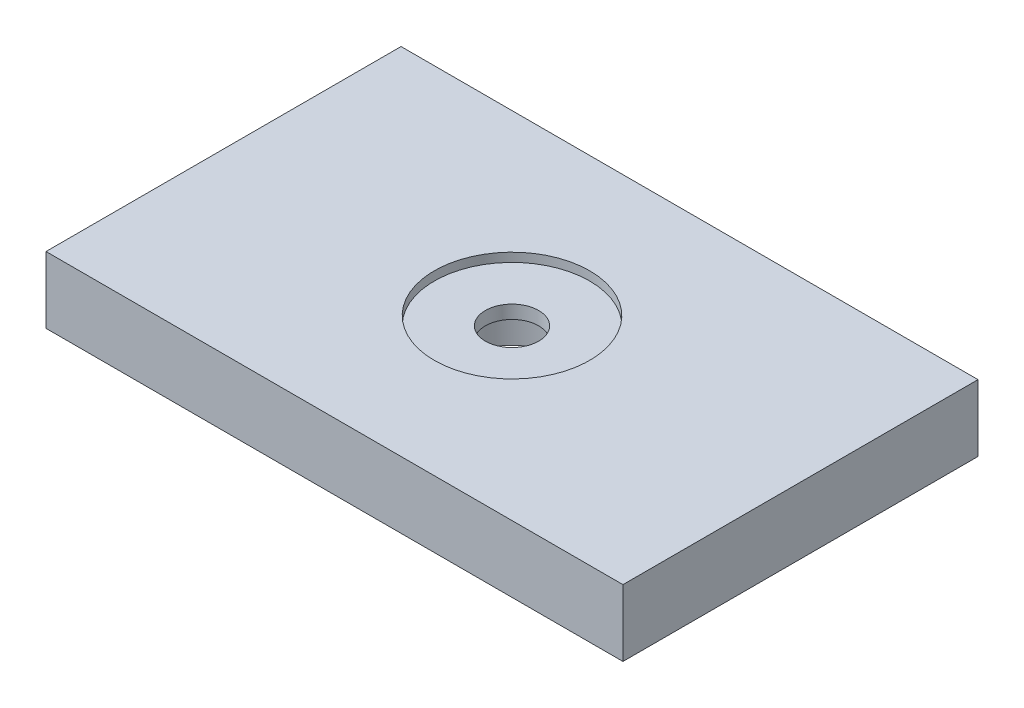
SolidWorks part; units mm, degrees
ref_plane "Спереди" through (0, 0, 0) normal (0, 0, 1) x (1, 0, 0)
ref_plane "Сверху" through (0, 0, 0) normal (0, 1, 0) x (1, 0, 0)
ref_plane "Справа" through (0, 0, 0) normal (1, 0, 0) x (0, 0, -1)
sketch "Эскиз4" plane through (0, 0, 0) normal (0, 1, 0) x (1, 0, 0)
  line L1 (-65, 40) -> (65, 40)
  line L2 (-65, 40) -> (-65, -40)
  line L3 (-65, -40) -> (65, -40)
  line L4 (65, 40) -> (65, -40)
  line L5 (-65, 40) -> (65, -40) construction
  line L6 (-65, -40) -> (65, 40) construction
  point P0 (0, 0)
extrude "Бобышка-Вытянуть3" add sketch "Эскиз4" along normal blind 15
sketch "Эскиз5" plane through (0, 15, 0) normal (0, 1, 0) x (1, 0, 0)
  circle A0 centre (0, 0) radius 17.5
extrude "Вырез-Вытянуть1" cut sketch "Эскиз5" against normal blind 2
sketch "Эскиз6" plane through (0, 0, 0) normal (0, -1, 0) x (1, 0, 0)
  circle A0 centre (0, 0) radius 13
extrude "Вырез-Вытянуть2" cut sketch "Эскиз6" against normal blind 10
sketch "Эскиз7" plane through (0, 13, 0) normal (0, 1, 0) x (1, 0, 0)
  circle A0 centre (0, 0) radius 6
extrude "Вырез-Вытянуть3" cut sketch "Эскиз7" against normal through all
